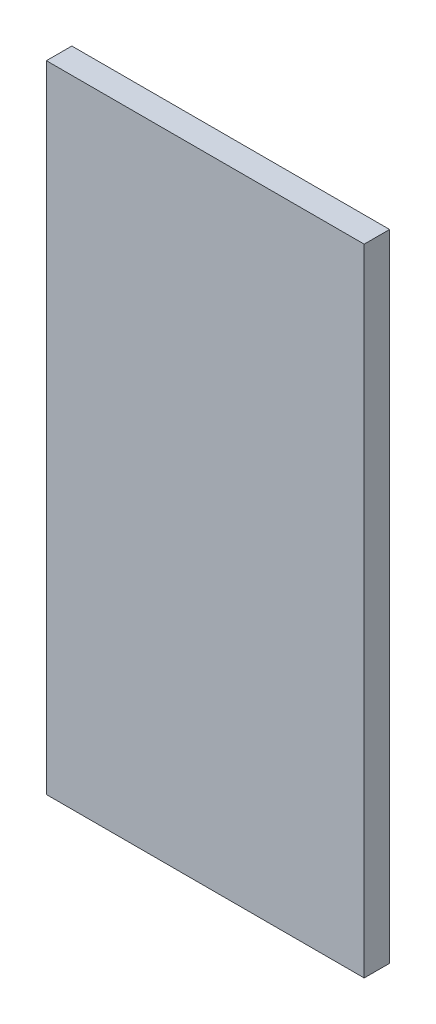
SolidWorks part; units mm, degrees
ref_plane "Front Plane" through (0, 0, 0) normal (0, 0, 1) x (1, 0, 0)
ref_plane "Top Plane" through (0, 0, 0) normal (0, 1, 0) x (1, 0, 0)
ref_plane "Right Plane" through (0, 0, 0) normal (1, 0, 0) x (0, 0, -1)
sketch "Sketch1" plane through (0, 0, 0) normal (0, 0, 1) x (1, 0, 0)
  circle A0 centre (0, 0) radius 17.5
  dimension "D1" = 35
extrude "Boss-Extrude1" add sketch "Sketch1" along normal blind 1.5
sketch "Sketch2" plane through (0, 0, 1.5) normal (0, 0, 1) x (1, 0, 0)
  circle A0 centre (0, 0) radius 40
  dimension "D1" = 80
extrude "Boss-Extrude2" add sketch "Sketch2" along normal blind 6.5
sketch "Sketch3" plane through (0, 0, 8) normal (0, 0, 1) x (1, 0, 0)
  line L1 (-125, -250) -> (125, -250)
  line L2 (-125, -250) -> (-125, 250)
  line L3 (-125, 250) -> (125, 250)
  line L4 (125, -250) -> (125, 250)
  line L5 (-125, -250) -> (125, 250) construction
  line L6 (-125, 250) -> (125, -250) construction
  point P0 (0, 0)
  dimension "D1" = 500
  dimension "D2" = 250
extrude "Boss-Extrude3" add sketch "Sketch3" along normal blind 20 contours L3 L4 L1 L2
fillet "Fillet2" radius 1 1 edges at (40, 0, 8)
